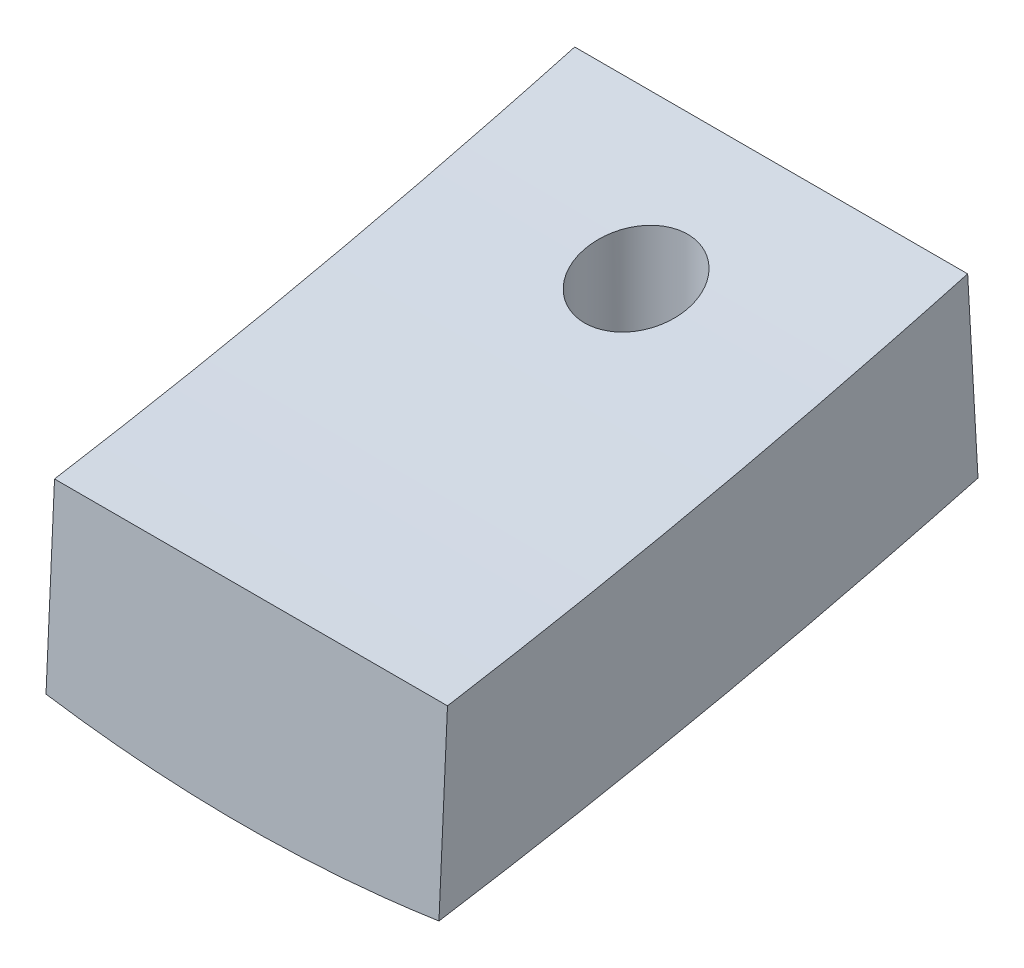
SolidWorks part; units mm, degrees
ref_plane "Front Plane" through (0, 0, 0) normal (0, 0, 1) x (1, 0, 0)
ref_plane "Top Plane" through (0, 0, 0) normal (0, 1, 0) x (1, 0, 0)
ref_plane "Right Plane" through (0, 0, 0) normal (1, 0, 0) x (0, 0, -1)
sketch "Sketch5" plane through (0, 0, 0) normal (1, 0, 0) x (0, 0, -1)
  line L0 (9.9972, -274.1407) -> (19.4463, -271.5305) construction
  line L1 (-1.0535, -276.6519) -> (9.9972, -274.1407) construction
  line L3 (-12.9922, -278.7632) -> (-1.0535, -276.6519) construction
  spline S0 degree 2 poles (12, -273.5874) (1.1187, -276.4811) (-10, -278.234) knots 0 0 0 1 1 1
  dimension "D1" = 22
  dimension "D2" = 12
sketch "Sketch2" plane through (0, 0, 0) normal (0, 0, 1) x (1, 0, 0)
  line L1 (-7.3278, -275.9901) -> (-9.4044, -275.7394) construction
  line L2 (7.3278, -275.9901) -> (9.438, -275.7351) construction
  line L3 (7.9997, -275.9089) -> (7.9997, -268.4866)
  line L4 (7.9997, -268.4866) -> (-8.0003, -268.4866)
  line L5 (-8.0003, -268.4866) -> (-8.0003, -275.9089)
  spline S0 degree 2 poles (7.9997, -275.9089) (-0.0003, -277.0643) (-8.0003, -275.9089) knots 0 0 0 1 1 1
  point P4 (-0.0003, -268.4866)
  dimension "D1" = 16
  dimension "D2" = 8
sweep "Sweep1" add profiles "Sketch2" path "Sketch5"
ref_plane "Plane1" through (0, -265.6699, 0) normal (0, 1, 0) x (1, 0, 0)
sketch "Sketch8" plane through (0, -265.6699, 0) normal (0, 1, 0) x (1, 0, 0)
  line L0 (0, 10.5954) -> (0, -0.5697) construction
  line L1 (7.9997, 11.5502) -> (-8.0003, 11.5502) construction
  circle A0 centre (0, 6.0502) radius 2.1
  dimension "D2" = 4.2
  dimension "D1" = 5.5
extrude "Cut-Extrude2" cut sketch "Sketch8" against normal through all
